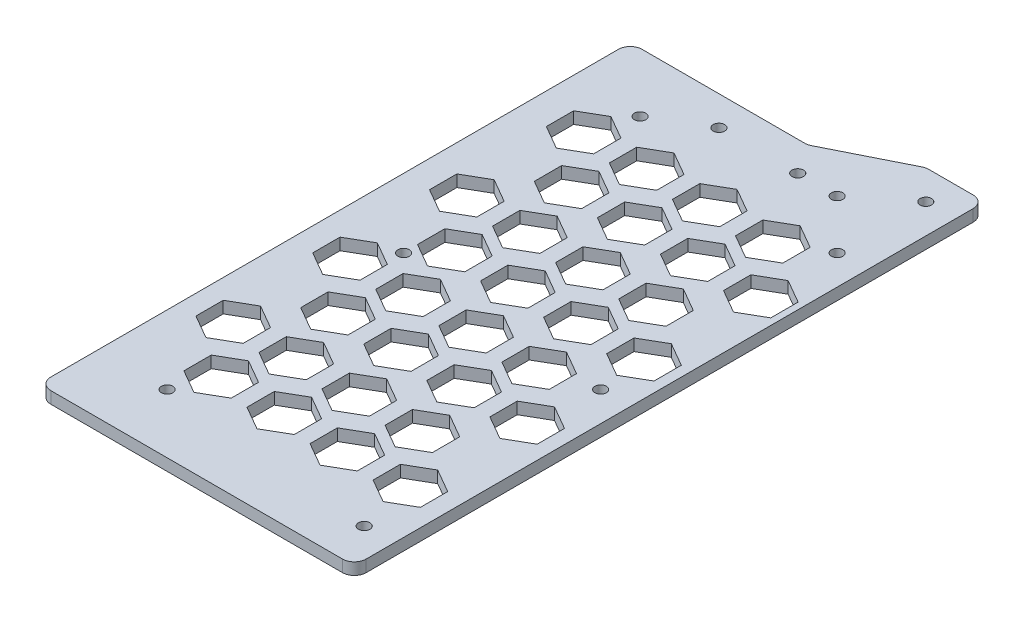
SolidWorks part; units mm, degrees
material "Thornel Mat VMA"
ref_plane "前视基准面" through (0, 0, 0) normal (0, 0, 1) x (1, 0, 0)
ref_plane "上视基准面" through (0, 0, 0) normal (0, 1, 0) x (1, 0, 0)
ref_plane "右视基准面" through (0, 0, 0) normal (1, 0, 0) x (0, 0, -1)
other "Configuration Table"
sketch "草图1" plane through (0, 0, 0) normal (0, 1, 0) x (1, 0, 0)
  line L0 (-40, 75) -> (5, 75)
  line L1 (-40, -75) -> (40, -75)
  line L2 (-40, -75) -> (-40, 75)
  line L3 (-40, 75) -> (40, 75) construction
  line L4 (40, -75) -> (40, 75)
  line L5 (-40, -75) -> (40, 75) construction
  line L6 (-40, 75) -> (40, -75) construction
  line L7 (5, 75) -> (25, 85)
  line L8 (25, 85) -> (40, 85)
  line L9 (40, 85) -> (40, 75)
  point P0 (0, 0)
  dimension "D1" = 80
  dimension "D2" = 150
  dimension "D3" = 15
  dimension "D4" = 10
  dimension "D5" = 35
extrude "凸台-拉伸1" add sketch "草图1" along normal blind 3
sketch "草图4" plane through (0, 3, 0) normal (0, 1, 0) x (1, 0, 0)
  line L0 (-40, -75) -> (40, -75) construction
  line L1 (-40, 75) -> (-5, 75) construction
  line L2 (-40, 75) -> (-40, -75) construction
  line L3 (-40, -75) -> (-5, -75) construction
  line L4 (-5, 75) -> (-5, -75) construction
  line L5 (-54.1369, 67.5) -> (53.5664, 67.5) construction
  line L6 (25, 85) -> (40, 85) construction
  line L7 (25, 85) -> (25, -75) construction
  line L8 (25, -75) -> (40, -75) construction
  line L9 (40, 85) -> (40, -75) construction
  line L10 (-40, 75) -> (40, 75) construction
  line L11 (-40, 75) -> (-40, 60) construction
  line L12 (-40, 60) -> (40, 60) construction
  line L13 (40, 75) -> (40, 60) construction
  line L14 (-22.5, 82.8681) -> (-22.5, -85.8747) construction
  line L15 (32.5, 89.0291) -> (32.5, -83.5928) construction
  circle A0 centre (32.5, 77.5) radius 1.45
  circle A1 centre (32.5, 55) radius 1.45
  circle A2 centre (20, 67.5) radius 1.45
  circle A3 centre (10, 67.5) radius 1.45
  circle A4 centre (32.5, -5) radius 1.45
  circle A5 centre (32.5, -65) radius 1.45
  circle A6 centre (-22.5, -60) radius 1.45
  circle A7 centre (-22.5, 0) radius 1.45
  circle A8 centre (-22.5, 60) radius 1.45
  circle A10 centre (-10, 67.5) radius 1.45
  dimension "D3" = 2.9
  dimension "D4" = 10
  dimension "D5" = 15
  dimension "D6" = 60
  dimension "D7" = 60
  dimension "D8" = 60
  dimension "D9" = 60
  dimension "D10" = 5
  dimension "D11" = 10
  dimension "D12" = 17.5
  dimension "D13" = 20
  dimension "D1" = 15
  dimension "D2" = 17.5
extrude "切除-拉伸1" cut sketch "草图4" against normal through all
sketch "草图5" plane through (0, 3, 0) normal (0, 1, 0) x (1, 0, 0)
  line L12 (-20.1751, 52.815) -> (-26.1751, 56.2791)
  line L13 (-26.1751, 56.2791) -> (-32.1751, 52.815)
  line L14 (-32.1751, 52.815) -> (-32.1751, 45.8868)
  line L15 (-32.1751, 45.8868) -> (-26.1751, 42.4227)
  line L16 (-26.1751, 42.4227) -> (-20.1751, 45.8868)
  line L17 (-20.1751, 45.8868) -> (-20.1751, 52.815)
  line L18 (-4.1751, 52.815) -> (-10.1751, 56.2791)
  line L19 (-9.6611, 39.2553) -> (-15.6611, 42.7194)
  line L20 (-15.6611, 42.7194) -> (-21.6611, 39.2553)
  line L21 (-21.6611, 39.2553) -> (-21.6611, 32.3271)
  line L22 (-21.6611, 32.3271) -> (-15.6611, 28.863)
  line L23 (-15.6611, 28.863) -> (-9.6611, 32.3271)
  line L24 (-9.6611, 32.3271) -> (-9.6611, 39.2553)
  line L25 (-10.1751, 56.2791) -> (-16.1751, 52.815)
  line L26 (-16.1751, 52.815) -> (-16.1751, 45.8868)
  line L27 (-16.1751, 45.8868) -> (-10.1751, 42.4227)
  line L28 (-10.1751, 42.4227) -> (-4.1751, 45.8868)
  line L29 (-4.1751, 45.8868) -> (-4.1751, 52.815)
  line L30 (6.3389, 39.2553) -> (0.3389, 42.7194)
  line L31 (0.3389, 42.7194) -> (-5.6611, 39.2553)
  line L32 (-5.6611, 39.2553) -> (-5.6611, 32.3271)
  line L33 (-5.6611, 32.3271) -> (0.3389, 28.863)
  line L34 (0.3389, 28.863) -> (6.3389, 32.3271)
  line L35 (6.3389, 32.3271) -> (6.3389, 39.2553)
  line L36 (11.8249, 52.815) -> (5.8249, 56.2791)
  line L37 (5.8249, 56.2791) -> (-0.1751, 52.815)
  line L38 (-0.1751, 52.815) -> (-0.1751, 45.8868)
  line L39 (-0.1751, 45.8868) -> (5.8249, 42.4227)
  line L40 (5.8249, 42.4227) -> (11.8249, 45.8868)
  line L41 (11.8249, 45.8868) -> (11.8249, 52.815)
  line L42 (22.3389, 39.2553) -> (16.3389, 42.7194)
  line L43 (16.3389, 42.7194) -> (10.3389, 39.2553)
  line L44 (10.3389, 39.2553) -> (10.3389, 32.3271)
  line L45 (10.3389, 32.3271) -> (16.3389, 28.863)
  line L46 (16.3389, 28.863) -> (22.3389, 32.3271)
  line L47 (22.3389, 32.3271) -> (22.3389, 39.2553)
  line L48 (27.8249, 52.815) -> (21.8249, 56.2791)
  line L49 (21.8249, 56.2791) -> (15.8249, 52.815)
  line L50 (15.8249, 52.815) -> (15.8249, 45.8868)
  line L51 (15.8249, 45.8868) -> (21.8249, 42.4227)
  line L52 (21.8249, 42.4227) -> (27.8249, 45.8868)
  line L53 (27.8249, 45.8868) -> (27.8249, 52.815)
  line L54 (38.3389, 39.2553) -> (32.3389, 42.7194)
  line L55 (32.3389, 42.7194) -> (26.3389, 39.2553)
  line L56 (26.3389, 39.2553) -> (26.3389, 32.3271)
  line L57 (26.3389, 32.3271) -> (32.3389, 28.863)
  line L58 (32.3389, 28.863) -> (38.3389, 32.3271)
  line L59 (38.3389, 32.3271) -> (38.3389, 39.2553)
  line L60 (-5.1145, 24.1185) -> (-11.1145, 27.5826)
  line L61 (-11.1145, 27.5826) -> (-17.1145, 24.1185)
  line L62 (-17.1145, 24.1185) -> (-17.1145, 17.1903)
  line L63 (-17.1145, 17.1903) -> (-11.1145, 13.7262)
  line L64 (-11.1145, 13.7262) -> (-5.1145, 17.1903)
  line L65 (-5.1145, 17.1903) -> (-5.1145, 24.1185)
  line L66 (5.3995, 10.5589) -> (-0.6005, 14.023)
  line L67 (-0.6005, 14.023) -> (-6.6005, 10.5589)
  line L68 (-6.6005, 10.5589) -> (-6.6005, 3.6306)
  line L69 (-6.6005, 3.6306) -> (-0.6005, 0.1665)
  line L70 (-0.6005, 0.1665) -> (5.3995, 3.6306)
  line L71 (5.3995, 3.6306) -> (5.3995, 10.5589)
  line L72 (10.8855, 24.1185) -> (4.8855, 27.5826)
  line L73 (4.8855, 27.5826) -> (-1.1145, 24.1185)
  line L74 (-1.1145, 24.1185) -> (-1.1145, 17.1903)
  line L75 (-1.1145, 17.1903) -> (4.8855, 13.7262)
  line L76 (4.8855, 13.7262) -> (10.8855, 17.1903)
  line L77 (10.8855, 17.1903) -> (10.8855, 24.1185)
  line L78 (21.3995, 10.5589) -> (15.3995, 14.023)
  line L79 (15.3995, 14.023) -> (9.3995, 10.5589)
  line L80 (9.3995, 10.5589) -> (9.3995, 3.6306)
  line L81 (9.3995, 3.6306) -> (15.3995, 0.1665)
  line L82 (15.3995, 0.1665) -> (21.3995, 3.6306)
  line L83 (21.3995, 3.6306) -> (21.3995, 10.5589)
  line L84 (26.8855, 24.1185) -> (20.8855, 27.5826)
  line L85 (20.8855, 27.5826) -> (14.8855, 24.1185)
  line L86 (14.8855, 24.1185) -> (14.8855, 17.1903)
  line L87 (14.8855, 17.1903) -> (20.8855, 13.7262)
  line L88 (20.8855, 13.7262) -> (26.8855, 17.1903)
  line L89 (26.8855, 17.1903) -> (26.8855, 24.1185)
  line L90 (37.3995, 10.5589) -> (31.3995, 14.023)
  line L91 (31.3995, 14.023) -> (25.3995, 10.5589)
  line L92 (25.3995, 10.5589) -> (25.3995, 3.6306)
  line L93 (25.3995, 3.6306) -> (31.3995, 0.1665)
  line L94 (31.3995, 0.1665) -> (37.3995, 3.6306)
  line L95 (37.3995, 3.6306) -> (37.3995, 10.5589)
  line L96 (-6.0539, -4.578) -> (-12.0539, -1.1139)
  line L97 (-12.0539, -1.1139) -> (-18.0539, -4.578)
  line L98 (-18.0539, -4.578) -> (-18.0539, -11.5062)
  line L99 (-18.0539, -11.5062) -> (-12.0539, -14.9703)
  line L100 (-12.0539, -14.9703) -> (-6.0539, -11.5062)
  line L101 (-6.0539, -11.5062) -> (-6.0539, -4.578)
  line L102 (4.4601, -18.1376) -> (-1.5399, -14.6735)
  line L103 (-1.5399, -14.6735) -> (-7.5399, -18.1376)
  line L104 (-7.5399, -18.1376) -> (-7.5399, -25.0658)
  line L105 (-7.5399, -25.0658) -> (-1.5399, -28.5299)
  line L106 (-1.5399, -28.5299) -> (4.4601, -25.0658)
  line L107 (4.4601, -25.0658) -> (4.4601, -18.1376)
  line L108 (9.9461, -4.578) -> (3.9461, -1.1139)
  line L109 (3.9461, -1.1139) -> (-2.0539, -4.578)
  line L110 (-2.0539, -4.578) -> (-2.0539, -11.5062)
  line L111 (-2.0539, -11.5062) -> (3.9461, -14.9703)
  line L112 (3.9461, -14.9703) -> (9.9461, -11.5062)
  line L113 (9.9461, -11.5062) -> (9.9461, -4.578)
  line L114 (20.4601, -18.1376) -> (14.4601, -14.6735)
  line L115 (14.4601, -14.6735) -> (8.4601, -18.1376)
  line L116 (8.4601, -18.1376) -> (8.4601, -25.0658)
  line L117 (8.4601, -25.0658) -> (14.4601, -28.5299)
  line L118 (14.4601, -28.5299) -> (20.4601, -25.0658)
  line L119 (20.4601, -25.0658) -> (20.4601, -18.1376)
  line L120 (25.9461, -4.578) -> (19.9461, -1.1139)
  line L121 (19.9461, -1.1139) -> (13.9461, -4.578)
  line L122 (13.9461, -4.578) -> (13.9461, -11.5062)
  line L123 (13.9461, -11.5062) -> (19.9461, -14.9703)
  line L124 (19.9461, -14.9703) -> (25.9461, -11.5062)
  line L125 (25.9461, -11.5062) -> (25.9461, -4.578)
  line L126 (36.4601, -18.1376) -> (30.4601, -14.6735)
  line L127 (30.4601, -14.6735) -> (24.4601, -18.1376)
  line L128 (24.4601, -18.1376) -> (24.4601, -25.0658)
  line L129 (24.4601, -25.0658) -> (30.4601, -28.5299)
  line L130 (30.4601, -28.5299) -> (36.4601, -25.0658)
  line L131 (36.4601, -25.0658) -> (36.4601, -18.1376)
  line L132 (-6.9933, -33.2745) -> (-12.9933, -29.8104)
  line L133 (-12.9933, -29.8104) -> (-18.9933, -33.2745)
  line L134 (-18.9933, -33.2745) -> (-18.9933, -40.2027)
  line L135 (-18.9933, -40.2027) -> (-12.9933, -43.6668)
  line L136 (-12.9933, -43.6668) -> (-6.9933, -40.2027)
  line L137 (-6.9933, -40.2027) -> (-6.9933, -33.2745)
  line L138 (3.5207, -46.8341) -> (-2.4793, -43.37)
  line L139 (-2.4793, -43.37) -> (-8.4793, -46.8341)
  line L140 (-8.4793, -46.8341) -> (-8.4793, -53.7623)
  line L141 (-8.4793, -53.7623) -> (-2.4793, -57.2264)
  line L142 (-2.4793, -57.2264) -> (3.5207, -53.7623)
  line L143 (3.5207, -53.7623) -> (3.5207, -46.8341)
  line L144 (9.0067, -33.2745) -> (3.0067, -29.8104)
  line L145 (3.0067, -29.8104) -> (-2.9933, -33.2745)
  line L146 (-2.9933, -33.2745) -> (-2.9933, -40.2027)
  line L147 (-2.9933, -40.2027) -> (3.0067, -43.6668)
  line L148 (3.0067, -43.6668) -> (9.0067, -40.2027)
  line L149 (9.0067, -40.2027) -> (9.0067, -33.2745)
  line L150 (19.5207, -46.8341) -> (13.5207, -43.37)
  line L151 (13.5207, -43.37) -> (7.5207, -46.8341)
  line L152 (7.5207, -46.8341) -> (7.5207, -53.7623)
  line L153 (7.5207, -53.7623) -> (13.5207, -57.2264)
  line L154 (13.5207, -57.2264) -> (19.5207, -53.7623)
  line L155 (19.5207, -53.7623) -> (19.5207, -46.8341)
  line L156 (25.0067, -33.2745) -> (19.0067, -29.8104)
  line L157 (19.0067, -29.8104) -> (13.0067, -33.2745)
  line L158 (13.0067, -33.2745) -> (13.0067, -40.2027)
  line L159 (13.0067, -40.2027) -> (19.0067, -43.6668)
  line L160 (19.0067, -43.6668) -> (25.0067, -40.2027)
  line L161 (25.0067, -40.2027) -> (25.0067, -33.2745)
  line L162 (35.5207, -46.8341) -> (29.5207, -43.37)
  line L163 (29.5207, -43.37) -> (23.5207, -46.8341)
  line L164 (23.5207, -46.8341) -> (23.5207, -53.7623)
  line L165 (23.5207, -53.7623) -> (29.5207, -57.2264)
  line L166 (29.5207, -57.2264) -> (35.5207, -53.7623)
  line L167 (35.5207, -53.7623) -> (35.5207, -46.8341)
  line L168 (-21.1145, 24.1185) -> (-27.1145, 27.5826)
  line L169 (-27.1145, 27.5826) -> (-33.1145, 24.1185)
  line L170 (-33.1145, 24.1185) -> (-33.1145, 17.1903)
  line L171 (-33.1145, 17.1903) -> (-27.1145, 13.7262)
  line L172 (-27.1145, 13.7262) -> (-21.1145, 17.1903)
  line L173 (-21.1145, 17.1903) -> (-21.1145, 24.1185)
  line L174 (-10.6005, 10.5589) -> (-16.6005, 14.023)
  line L175 (-16.6005, 14.023) -> (-22.6005, 10.5589)
  line L176 (-22.6005, 10.5589) -> (-22.6005, 3.6306)
  line L177 (-22.6005, 3.6306) -> (-16.6005, 0.1665)
  line L178 (-16.6005, 0.1665) -> (-10.6005, 3.6306)
  line L179 (-10.6005, 3.6306) -> (-10.6005, 10.5589)
  line L180 (-22.0539, -4.578) -> (-28.0539, -1.1139)
  line L181 (-28.0539, -1.1139) -> (-34.0539, -4.578)
  line L182 (-34.0539, -4.578) -> (-34.0539, -11.5062)
  line L183 (-34.0539, -11.5062) -> (-28.0539, -14.9703)
  line L184 (-28.0539, -14.9703) -> (-22.0539, -11.5062)
  line L185 (-22.0539, -11.5062) -> (-22.0539, -4.578)
  line L186 (-11.5399, -18.1376) -> (-17.5399, -14.6735)
  line L187 (-17.5399, -14.6735) -> (-23.5399, -18.1376)
  line L188 (-23.5399, -18.1376) -> (-23.5399, -25.0658)
  line L189 (-23.5399, -25.0658) -> (-17.5399, -28.5299)
  line L190 (-17.5399, -28.5299) -> (-11.5399, -25.0658)
  line L191 (-11.5399, -25.0658) -> (-11.5399, -18.1376)
  line L192 (-22.9933, -33.2745) -> (-28.9933, -29.8104)
  line L193 (-28.9933, -29.8104) -> (-34.9933, -33.2745)
  line L194 (-34.9933, -33.2745) -> (-34.9933, -40.2027)
  line L195 (-34.9933, -40.2027) -> (-28.9933, -43.6668)
  line L196 (-28.9933, -43.6668) -> (-22.9933, -40.2027)
  line L197 (-22.9933, -40.2027) -> (-22.9933, -33.2745)
  line L198 (-12.4793, -46.8341) -> (-18.4793, -43.37)
  line L199 (-18.4793, -43.37) -> (-24.4793, -46.8341)
  line L200 (-24.4793, -46.8341) -> (-24.4793, -53.7623)
  line L201 (-24.4793, -53.7623) -> (-18.4793, -57.2264)
  line L202 (-18.4793, -57.2264) -> (-12.4793, -53.7623)
  line L203 (-12.4793, -53.7623) -> (-12.4793, -46.8341)
  circle A0 centre (-26.1751, 49.3509) radius 6 construction
  circle A1 centre (-15.6611, 35.7912) radius 6 construction
  point P2 (-19.2547, 12.3225)
  point P17 (-16.6005, 14.023)
  dimension "D2" = 12
  dimension "D1" = 12
  dimension "D3" = 5
  dimension "D4" = 4
  dimension "D5" = 4
extrude "切除-拉伸2" cut sketch "草图5" against normal through all
fillet "圆角1" radius 3 6 edges at (40, 1.5, 75) (-40, 1.5, 75) (-40, 1.5, -75) (5, 1.5, -75) (40, 1.5, -85) (25, 1.5, -85)
